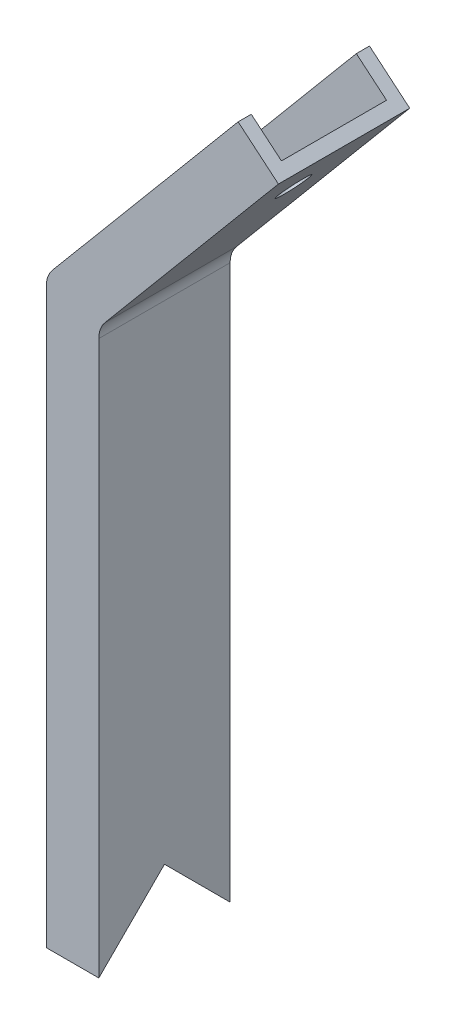
SolidWorks part; units mm, degrees
material "Alloy Steel"
ref_plane "Front Plane" through (0, 0, 0) normal (0, 0, 1) x (1, 0, 0)
ref_plane "Top Plane" through (0, 0, 0) normal (0, 1, 0) x (1, 0, 0)
ref_plane "Right Plane" through (0, 0, 0) normal (1, 0, 0) x (0, 0, -1)
sketch "Sketch1" plane through (0, 0, 0) normal (0, 0, 1) x (1, 0, 0)
  line L0 (0, -141.9681) -> (0, 91.0319) construction
  line L1 (0, 91.0319) -> (70.7066, 175.2968) construction
  line L2 (10, -141.9681) -> (10, 87.3922)
  line L3 (10, 87.3922) -> (78.3671, 168.869)
  line L4 (-10, -141.9681) -> (-10, 94.6716)
  line L5 (-10, 94.6716) -> (63.0462, 181.7247)
  line L6 (10, -141.9681) -> (-10, -141.9681)
  line L7 (78.3671, 168.869) -> (63.0462, 181.7247)
  dimension "D1" = 233
  dimension "D2" = 110
  dimension "D3" = 140
  dimension "D4" = 10
  dimension "D5" = 10
extrude "Boss-Extrude1" add sketch "Sketch1" along normal blind 50
sketch "Sketch2" plane through (0, -141.9681, 0) normal (0, -1, 0) x (1, 0, 0)
  line L0 (-10, 45) -> (5, 45)
  line L1 (-10, 50) -> (-10, 0) construction
  line L2 (5, 45) -> (5, 5)
  line L3 (5, 5) -> (-10, 5)
  line L4 (-10, 5) -> (-10, 45)
  line L5 (-10, 50) -> (10, 50) construction
  dimension "D1" = 5
  dimension "D2" = 40
  dimension "D3" = 15
extrude "Cut-Extrude1" cut sketch "Sketch2" against normal up to body contours L4 L0 L2 L3
sketch "Sketch3" plane through (115.5311, 137.6846, 0) normal (0.6428, 0.766, 0) x (0.766, -0.6428, 0)
  line L0 (-68.5142, -5) -> (-53.5142, -5)
  line L1 (-68.5142, -50) -> (-68.5142, 0) construction
  line L2 (-53.5142, -5) -> (-53.5142, -45)
  line L3 (-53.5142, -45) -> (-68.5142, -45)
  line L4 (-68.5142, -45) -> (-68.5142, -5)
  line L5 (-48.5142, 0) -> (-68.5142, 0) construction
  line L6 (-48.5142, -50) -> (-68.5142, -50) construction
  dimension "D1" = 5
  dimension "D2" = 5
  dimension "D3" = 15
extrude "Cut-Extrude2" cut sketch "Sketch3" against normal up to vertex contours L4 L0 L2 L3
fillet "Fillet1" radius 10 4 edges at (10, 87.3922, 25) (5, 89.2121, 25) (-10, 94.6716, 47.5) (-10, 94.6716, 2.5)
sketch "Sketch4" plane through (-10, 0, 0) normal (-1, 0, 0) x (0, 0, 1)
  line L0 (25, 85.5724) -> (25, -141.9681) construction
  line L1 (45, 85.5724) -> (5, 85.5724) construction
  line L2 (45, -141.9681) -> (5, -141.9681) construction
  line L3 (0, -141.9681) -> (25, -102.0818)
  line L4 (25, -102.0818) -> (50, -141.9681)
  line L5 (50, -141.9681) -> (0, -141.9681)
  dimension "D1" = 47.0735
extrude "Cut-Extrude3" cut sketch "Sketch4" against normal up to next
sketch "Sketch7" plane through (-40.9943, 34.3983, 0) normal (-0.766, 0.6428, 0) x (0, 0, 1)
  line L0 (25, 179.7345) -> (25, 75.1941) construction
  line L1 (5, 179.7345) -> (45, 179.7345) construction
  line L2 (5, 75.1941) -> (45, 75.1941) construction
  circle A0 centre (25, 149.7345) radius 6
  dimension "D1" = 30
  dimension "D2" = 12
extrude "Cut-Extrude8" cut sketch "Sketch7" against normal up to next
sketch "Sketch10" plane through (-10, 0, 0) normal (-1, 0, 0) x (0, 0, 1)
  line L0 (50, -127.0818) -> (25, -102.0818)
  line L1 (50, 91.0319) -> (50, -141.9681) construction
  line L2 (25, -102.0818) -> (99.2462, -176.328) construction
  line L3 (25, -102.0818) -> (0, -127.0818)
  line L4 (0, 91.0319) -> (0, -141.9681) construction
  line L5 (-49.2462, -176.328) -> (25, -102.0818) construction
  line L6 (0, -127.0818) -> (0, -141.9681)
  line L7 (0, -141.9681) -> (50, -141.9681)
  line L8 (50, -141.9681) -> (50, -127.0818)
extrude "Cut-Extrude9" cut sketch "Sketch10" against normal up to vertex
